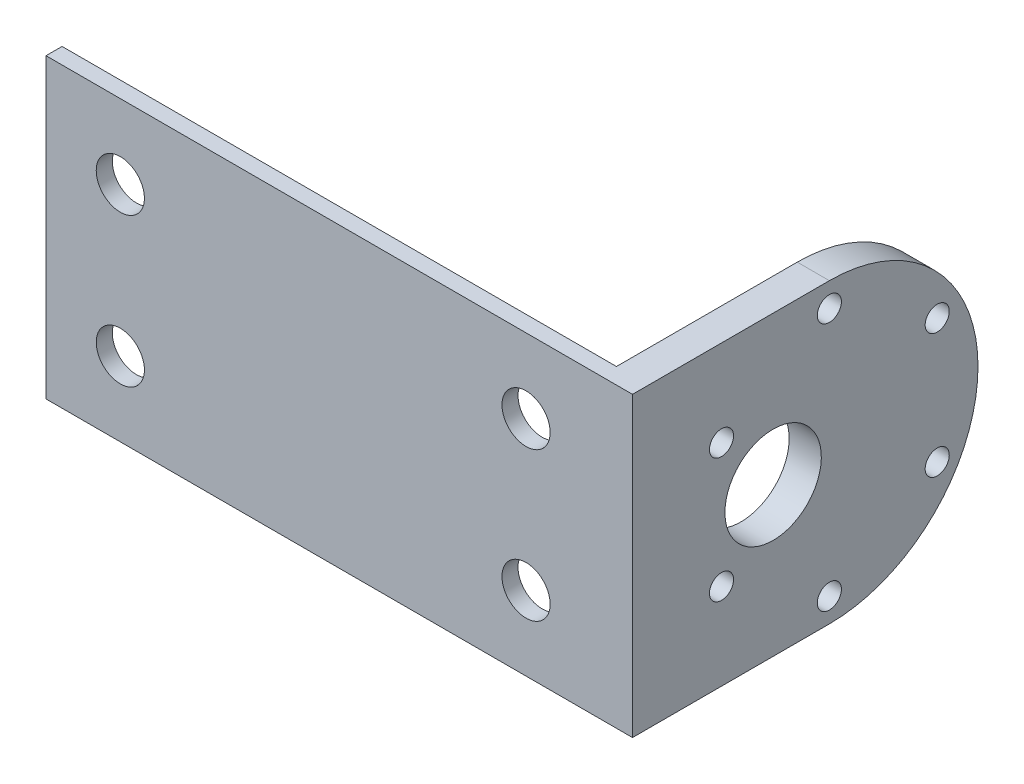
SolidWorks part; units mm, degrees
ref_plane "前视基准面" through (0, 0, 0) normal (0, 0, 1) x (1, 0, 0)
ref_plane "上视基准面" through (0, 0, 0) normal (0, 1, 0) x (1, 0, 0)
ref_plane "右视基准面" through (0, 0, 0) normal (1, 0, 0) x (0, 0, -1)
sketch "草图2" plane through (0, 0, 0) normal (0, 0, 1) x (1, 0, 0)
  line L0 (0, -18.5) -> (0, 18.5) construction
  line L1 (-34.5, 18.5) -> (34.5, 18.5)
  line L2 (-34.5, 18.5) -> (-34.5, -18.5)
  line L3 (-34.5, -18.5) -> (34.5, -18.5)
  line L4 (34.5, 18.5) -> (34.5, -18.5)
  line L5 (-34.5, 18.5) -> (34.5, -18.5) construction
  line L6 (-34.5, -18.5) -> (34.5, 18.5) construction
  line L7 (34.5, 0) -> (-34.5, 0) construction
  line L8 (34.5, 9.25) -> (25.25, 9.25) construction
  circle A0 centre (25.25, 9.25) radius 3
  circle A1 centre (25.25, -9.25) radius 3
  circle A2 centre (-25.25, 9.25) radius 3
  circle A3 centre (-25.25, -9.25) radius 3
  point P0 (0, 0)
extrude "凸台-拉伸1" add sketch "草图2" along normal blind 2
ref_plane "基准面4" through (34.5, 0, 0) normal (1, 0, 0) x (0, 0, -1)
sketch "草图3" plane through (34.5, 0, 0) normal (1, 0, 0) x (0, 0, -1)
  line L0 (0, 0) -> (42, 0) construction
  line L1 (4, 18.5) -> (22.5, 18.5) construction
  line L3 (-2, 18.5) -> (0, 18.5) construction
  line L4 (22.5, 18.5) -> (22.5, 0) construction
  line L5 (22.5, 18.5) -> (0, 18.5)
  line L6 (0, 18.5) -> (0, -18.5)
  line L7 (0, -18.5) -> (22.5, -18.5)
  line L8 (0, 18.5) -> (-2, 18.5)
  line L9 (-2, -18.5) -> (-2, 18.5) construction
  line L10 (0, -18.5) -> (-2, -18.5)
  line L11 (-2, -18.5) -> (-2, 18.5)
  line L12 (22.5, 0) -> (22.5, -15.5) construction
  line L13 (22.5, 0) -> (29.5, 0) construction
  circle A0 centre (22.5, 0) radius 18.5
  circle A1 centre (22.5, -15.5) radius 1.5
  circle A2 centre (9.0766, -7.75) radius 1.5
  circle A3 centre (9.0766, 7.75) radius 1.5
  circle A4 centre (22.5, 15.5) radius 1.5
  circle A5 centre (35.9234, 7.75) radius 1.5
  circle A6 centre (35.9234, -7.75) radius 1.5
  circle A8 centre (15.5, 0) radius 6
  point P31 (22.5, 0)
  dimension "D1" = 6
extrude "凸台-拉伸2" add sketch "草图3" along normal blind 4
